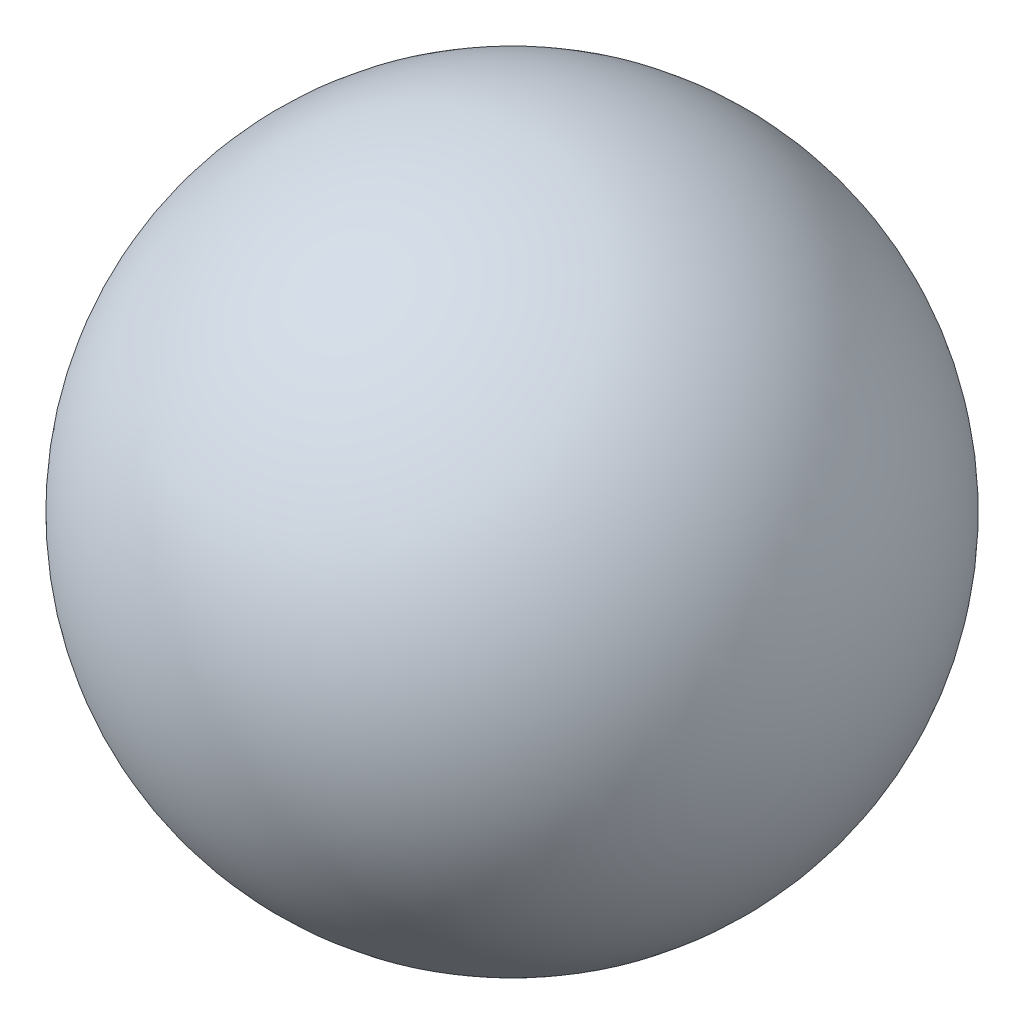
SolidWorks part; units mm, degrees
ref_plane "前视基准面" through (0, 0, 0) normal (0, 0, 1) x (1, 0, 0)
ref_plane "上视基准面" through (0, 0, 0) normal (0, 1, 0) x (1, 0, 0)
ref_plane "右视基准面" through (0, 0, 0) normal (1, 0, 0) x (0, 0, -1)
sketch "草图1" plane through (0, 0, 0) normal (0, 0, 1) x (1, 0, 0)
  line L0 (0, 296.3556) -> (0, -281.0191) construction
  line L1 (0, 105) -> (0, -105)
  arc A0 (0, -105) -> (0, 105) centre (0, 0) ccw
  dimension "D1" = 105
revolve "旋转1" add sketch "草图1" angle 360 about L0
